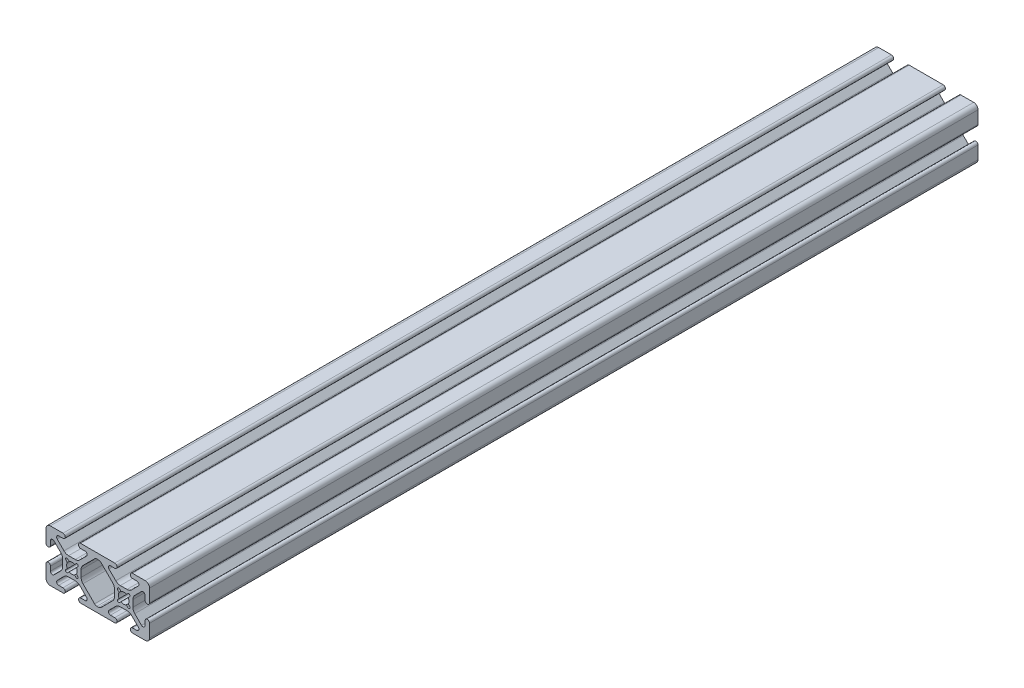
SolidWorks part; units mm, degrees
material "6105-T5 Aluminum"
ref_plane "Front Plane" through (0, 0, 0) normal (0, 0, 1) x (1, 0, 0)
ref_plane "Top Plane" through (0, 0, 0) normal (0, 1, 0) x (1, 0, 0)
ref_plane "Right Plane" through (0, 0, 0) normal (1, 0, 0) x (0, 0, -1)
sketch "Sketch1" plane through (0, 0, 0) normal (0, 0, 1) x (1, 0, 0)
  line L0 (-14.0405, -2.2319) -> (-14.6692, -2.8605)
  line L1 (-15.5605, -1.9692) -> (-14.9319, -1.3405)
  line L2 (-14.9319, 1.3405) -> (-15.5605, 1.9692)
  line L3 (-14.6692, 2.8605) -> (-14.0405, 2.2319)
  line L4 (-11.3595, 2.2319) -> (-10.7308, 2.8605)
  line L5 (-9.8395, 1.9692) -> (-10.4681, 1.3405)
  line L6 (-10.4681, -1.3405) -> (-9.8395, -1.9692)
  line L7 (-10.7308, -2.8605) -> (-11.3595, -2.2319)
  line L8 (14.6692, -2.8605) -> (14.0405, -2.2319)
  line L9 (11.3595, -2.2319) -> (10.7308, -2.8605)
  line L10 (9.8395, -1.9692) -> (10.4681, -1.3405)
  line L11 (10.4681, 1.3405) -> (9.8395, 1.9692)
  line L12 (10.7308, 2.8605) -> (11.3595, 2.2319)
  line L13 (14.0405, 2.2319) -> (14.6692, 2.8605)
  line L14 (15.5605, 1.9692) -> (14.9319, 1.3405)
  line L15 (14.9319, -1.3405) -> (15.5605, -1.9692)
  line L16 (-0.4522, 10.033) -> (0.4522, 10.033)
  line L17 (1.5658, 9.5718) -> (7.2529, 3.8846)
  line L18 (8.1828, 1.6396) -> (8.1828, -1.6396)
  line L19 (7.2529, -3.8846) -> (1.5658, -9.5718)
  line L20 (0.4522, -10.033) -> (-0.4522, -10.033)
  line L21 (-1.5658, -9.5718) -> (-7.2529, -3.8846)
  line L22 (-8.1828, -1.6396) -> (-8.1828, 1.6396)
  line L23 (-7.2529, 3.8846) -> (-1.5658, 9.5718)
  line L24 (8.3439, -10.4902) -> (6.2251, -10.4902)
  line L25 (5.5067, -8.7558) -> (8.8154, -5.4471)
  line L26 (11.0604, -4.5172) -> (14.3396, -4.5172)
  line L27 (16.5846, -5.4471) -> (19.8933, -8.7558)
  line L28 (19.1749, -10.4902) -> (17.0561, -10.4902)
  line L29 (17.0561, -12.7) -> (23.2918, -12.7)
  line L30 (25.4, -10.5918) -> (25.4, -4.3561)
  line L31 (23.1902, -4.3561) -> (23.1902, -6.4749)
  line L32 (21.4558, -7.1933) -> (18.1471, -3.8846)
  line L33 (17.2172, -1.6396) -> (17.2172, 1.6396)
  line L34 (18.1471, 3.8846) -> (21.4558, 7.1933)
  line L35 (23.1902, 6.4749) -> (23.1902, 4.3561)
  line L36 (25.4, 4.3561) -> (25.4, 10.5918)
  line L37 (23.2918, 12.7) -> (17.0561, 12.7)
  line L38 (17.0561, 10.4902) -> (19.1749, 10.4902)
  line L39 (19.8933, 8.7558) -> (16.5846, 5.4471)
  line L40 (14.3396, 4.5172) -> (11.0604, 4.5172)
  line L41 (8.8154, 5.4471) -> (5.5067, 8.7558)
  line L42 (6.2251, 10.4902) -> (8.3439, 10.4902)
  line L43 (8.3439, 12.7) -> (-8.3439, 12.7)
  line L44 (-8.3439, 10.4902) -> (-6.2251, 10.4902)
  line L45 (-5.5067, 8.7558) -> (-8.8154, 5.4471)
  line L46 (-11.0604, 4.5172) -> (-14.3396, 4.5172)
  line L47 (-16.5846, 5.4471) -> (-19.8933, 8.7558)
  line L48 (-19.1749, 10.4902) -> (-17.0561, 10.4902)
  line L49 (-17.0561, 12.7) -> (-23.2918, 12.7)
  line L50 (-25.4, 10.5918) -> (-25.4, 4.3561)
  line L51 (-23.1902, 4.3561) -> (-23.1902, 6.4749)
  line L52 (-21.4558, 7.1933) -> (-18.1471, 3.8846)
  line L53 (-17.2172, 1.6396) -> (-17.2172, -1.6396)
  line L54 (-18.1471, -3.8846) -> (-21.4558, -7.1933)
  line L55 (-23.1902, -6.4749) -> (-23.1902, -4.3561)
  line L56 (-25.4, -4.3561) -> (-25.4, -10.5918)
  line L57 (-23.2918, -12.7) -> (-17.0561, -12.7)
  line L58 (-17.0561, -10.4902) -> (-19.1749, -10.4902)
  line L59 (-19.8933, -8.7558) -> (-16.5846, -5.4471)
  line L60 (-14.3396, -4.5172) -> (-11.0604, -4.5172)
  line L61 (-8.8154, -5.4471) -> (-5.5067, -8.7558)
  line L62 (-6.2251, -10.4902) -> (-8.3439, -10.4902)
  line L63 (-8.3439, -12.7) -> (8.3439, -12.7)
  arc A0 (-15.5605, -1.9692) -> (-14.6692, -2.8605) centre (-15.1696, -2.4696) ccw
  arc A1 (-14.9319, 1.3405) -> (-14.9319, -1.3405) centre (-12.7, 0) ccw
  arc A2 (-14.6692, 2.8605) -> (-15.5605, 1.9692) centre (-15.1696, 2.4696) ccw
  arc A3 (-11.3595, 2.2319) -> (-14.0405, 2.2319) centre (-12.7, 0) ccw
  arc A4 (-9.8395, 1.9692) -> (-10.7308, 2.8605) centre (-10.2304, 2.4696) ccw
  arc A5 (-10.4681, -1.3405) -> (-10.4681, 1.3405) centre (-12.7, 0) ccw
  arc A6 (-10.7308, -2.8605) -> (-9.8395, -1.9692) centre (-10.2304, -2.4696) ccw
  arc A7 (-14.0405, -2.2319) -> (-11.3595, -2.2319) centre (-12.7, 0) ccw
  arc A8 (11.3595, -2.2319) -> (14.0405, -2.2319) centre (12.7, 0) ccw
  arc A9 (9.8395, -1.9692) -> (10.7308, -2.8605) centre (10.2304, -2.4696) ccw
  arc A10 (10.4681, 1.3405) -> (10.4681, -1.3405) centre (12.7, 0) ccw
  arc A11 (10.7308, 2.8605) -> (9.8395, 1.9692) centre (10.2304, 2.4696) ccw
  arc A12 (14.0405, 2.2319) -> (11.3595, 2.2319) centre (12.7, 0) ccw
  arc A13 (15.5605, 1.9692) -> (14.6692, 2.8605) centre (15.1696, 2.4696) ccw
  arc A14 (14.9319, -1.3405) -> (14.9319, 1.3405) centre (12.7, 0) ccw
  arc A15 (14.6692, -2.8605) -> (15.5605, -1.9692) centre (15.1696, -2.4696) ccw
  arc A16 (-0.4522, 10.033) -> (-1.5658, 9.5718) centre (-0.4522, 8.4582) ccw
  arc A17 (1.5658, 9.5718) -> (0.4522, 10.033) centre (0.4522, 8.4582) ccw
  arc A18 (8.1828, 1.6396) -> (7.2529, 3.8846) centre (5.0078, 1.6396) ccw
  arc A19 (7.2529, -3.8846) -> (8.1828, -1.6396) centre (5.0078, -1.6396) ccw
  arc A20 (0.4522, -10.033) -> (1.5658, -9.5718) centre (0.4522, -8.4582) ccw
  arc A21 (-1.5658, -9.5718) -> (-0.4522, -10.033) centre (-0.4522, -8.4582) ccw
  arc A22 (-8.1828, -1.6396) -> (-7.2529, -3.8846) centre (-5.0078, -1.6396) ccw
  arc A23 (-7.2529, 3.8846) -> (-8.1828, 1.6396) centre (-5.0078, 1.6396) ccw
  arc A24 (8.3439, -12.7) -> (8.3439, -10.4902) centre (8.3439, -11.5951) ccw
  arc A25 (5.5067, -8.7558) -> (6.2251, -10.4902) centre (6.2251, -9.4742) ccw
  arc A26 (11.0604, -4.5172) -> (8.8154, -5.4471) centre (11.0604, -7.6922) ccw
  arc A27 (16.5846, -5.4471) -> (14.3396, -4.5172) centre (14.3396, -7.6922) ccw
  arc A28 (19.1749, -10.4902) -> (19.8933, -8.7558) centre (19.1749, -9.4742) ccw
  arc A29 (17.0561, -10.4902) -> (17.0561, -12.7) centre (17.0561, -11.5951) ccw
  arc A30 (23.2918, -12.7) -> (25.4, -10.5918) centre (23.2918, -10.5918) ccw
  arc A31 (25.4, -4.3561) -> (23.1902, -4.3561) centre (24.2951, -4.3561) ccw
  arc A32 (21.4558, -7.1933) -> (23.1902, -6.4749) centre (22.1742, -6.4749) ccw
  arc A33 (17.2172, -1.6396) -> (18.1471, -3.8846) centre (20.3922, -1.6396) ccw
  arc A34 (18.1471, 3.8846) -> (17.2172, 1.6396) centre (20.3922, 1.6396) ccw
  arc A35 (23.1902, 6.4749) -> (21.4558, 7.1933) centre (22.1742, 6.4749) ccw
  arc A36 (23.1902, 4.3561) -> (25.4, 4.3561) centre (24.2951, 4.3561) ccw
  arc A37 (25.4, 10.5918) -> (23.2918, 12.7) centre (23.2918, 10.5918) ccw
  arc A38 (17.0561, 12.7) -> (17.0561, 10.4902) centre (17.0561, 11.5951) ccw
  arc A39 (19.8933, 8.7558) -> (19.1749, 10.4902) centre (19.1749, 9.4742) ccw
  arc A40 (14.3396, 4.5172) -> (16.5846, 5.4471) centre (14.3396, 7.6922) ccw
  arc A41 (8.8154, 5.4471) -> (11.0604, 4.5172) centre (11.0604, 7.6922) ccw
  arc A42 (6.2251, 10.4902) -> (5.5067, 8.7558) centre (6.2251, 9.4742) ccw
  arc A43 (8.3439, 10.4902) -> (8.3439, 12.7) centre (8.3439, 11.5951) ccw
  arc A44 (-8.3439, 12.7) -> (-8.3439, 10.4902) centre (-8.3439, 11.5951) ccw
  arc A45 (-5.5067, 8.7558) -> (-6.2251, 10.4902) centre (-6.2251, 9.4742) ccw
  arc A46 (-11.0604, 4.5172) -> (-8.8154, 5.4471) centre (-11.0604, 7.6922) ccw
  arc A47 (-16.5846, 5.4471) -> (-14.3396, 4.5172) centre (-14.3396, 7.6922) ccw
  arc A48 (-19.1749, 10.4902) -> (-19.8933, 8.7558) centre (-19.1749, 9.4742) ccw
  arc A49 (-17.0561, 10.4902) -> (-17.0561, 12.7) centre (-17.0561, 11.5951) ccw
  arc A50 (-23.2918, 12.7) -> (-25.4, 10.5918) centre (-23.2918, 10.5918) ccw
  arc A51 (-25.4, 4.3561) -> (-23.1902, 4.3561) centre (-24.2951, 4.3561) ccw
  arc A52 (-21.4558, 7.1933) -> (-23.1902, 6.4749) centre (-22.1742, 6.4749) ccw
  arc A53 (-17.2172, 1.6396) -> (-18.1471, 3.8846) centre (-20.3922, 1.6396) ccw
  arc A54 (-18.1471, -3.8846) -> (-17.2172, -1.6396) centre (-20.3922, -1.6396) ccw
  arc A55 (-23.1902, -6.4749) -> (-21.4558, -7.1933) centre (-22.1742, -6.4749) ccw
  arc A56 (-23.1902, -4.3561) -> (-25.4, -4.3561) centre (-24.2951, -4.3561) ccw
  arc A57 (-25.4, -10.5918) -> (-23.2918, -12.7) centre (-23.2918, -10.5918) ccw
  arc A58 (-17.0561, -12.7) -> (-17.0561, -10.4902) centre (-17.0561, -11.5951) ccw
  arc A59 (-19.8933, -8.7558) -> (-19.1749, -10.4902) centre (-19.1749, -9.4742) ccw
  arc A60 (-14.3396, -4.5172) -> (-16.5846, -5.4471) centre (-14.3396, -7.6922) ccw
  arc A61 (-8.8154, -5.4471) -> (-11.0604, -4.5172) centre (-11.0604, -7.6922) ccw
  arc A62 (-6.2251, -10.4902) -> (-5.5067, -8.7558) centre (-6.2251, -9.4742) ccw
  arc A63 (-8.3439, -10.4902) -> (-8.3439, -12.7) centre (-8.3439, -11.5951) ccw
extrude "Extrude1" add sketch "Sketch1" against normal blind 406.4
